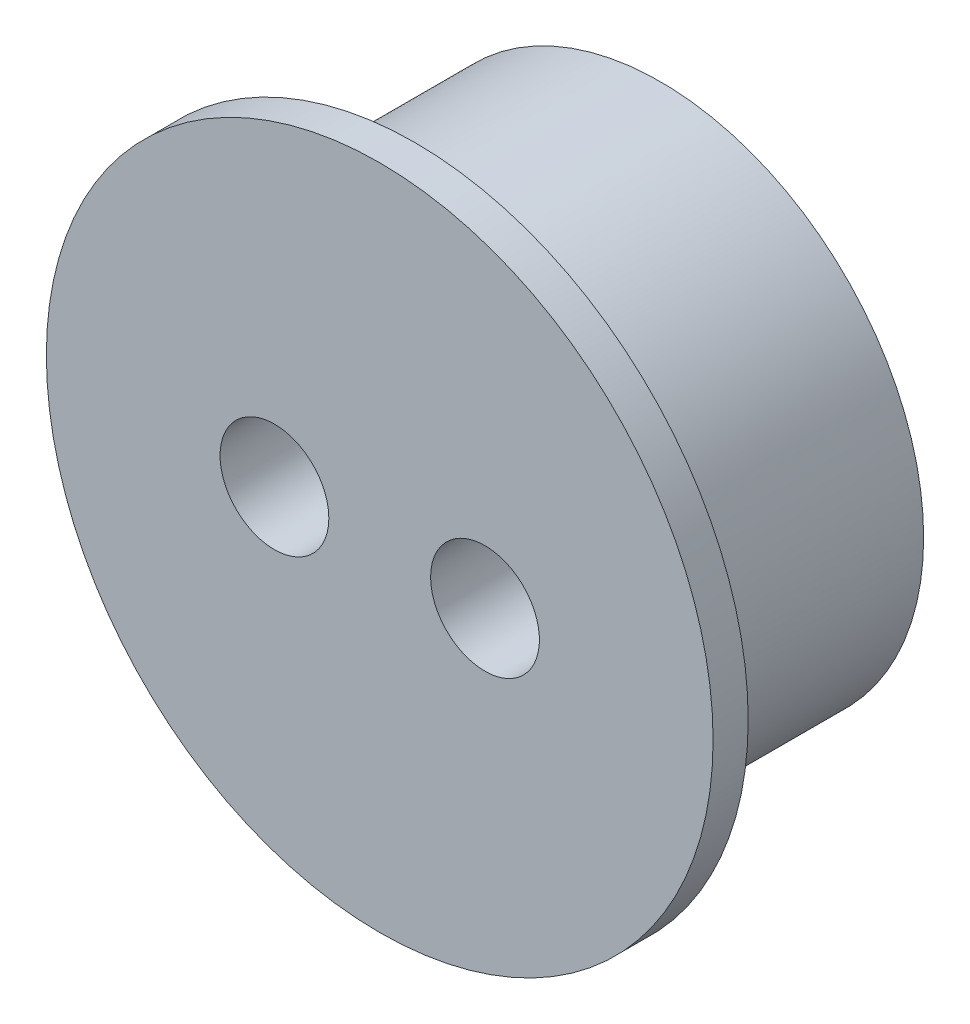
SolidWorks part; units mm, degrees
ref_plane "Front Plane" through (0, 0, 0) normal (0, 0, 1) x (1, 0, 0)
ref_plane "Top Plane" through (0, 0, 0) normal (0, 1, 0) x (1, 0, 0)
ref_plane "Right Plane" through (0, 0, 0) normal (1, 0, 0) x (0, 0, -1)
sketch "Sketch1" plane through (0, 0, 0) normal (0, 0, 1) x (1, 0, 0)
  circle A0 centre (0, 0) radius 7.5
  dimension "D1" = 15
extrude "Boss-Extrude1" add sketch "Sketch1" along normal blind 7
sketch "Sketch2" plane through (0, 0, 7) normal (0, 0, 1) x (1, 0, 0)
  circle A0 centre (0, 0) radius 9.5
  dimension "D1" = 19
extrude "Boss-Extrude2" add sketch "Sketch2" along normal blind 1
sketch "Sketch5" plane through (0, 0, 0) normal (0, 0, -1) x (-1, 0, 0)
  line L0 (-11.1934, 0) -> (10.4605, 0) construction
  line L1 (0, -10.4383) -> (0, 9.8609) construction
  circle A2 centre (-3, 0) radius 1.55
  circle A3 centre (3, 0) radius 1.55
  point P11 (0, 3.5355)
  dimension "D2" = 3
  dimension "D1" = 3.1
extrude "Cut-Extrude2" cut sketch "Sketch5" against normal through all
